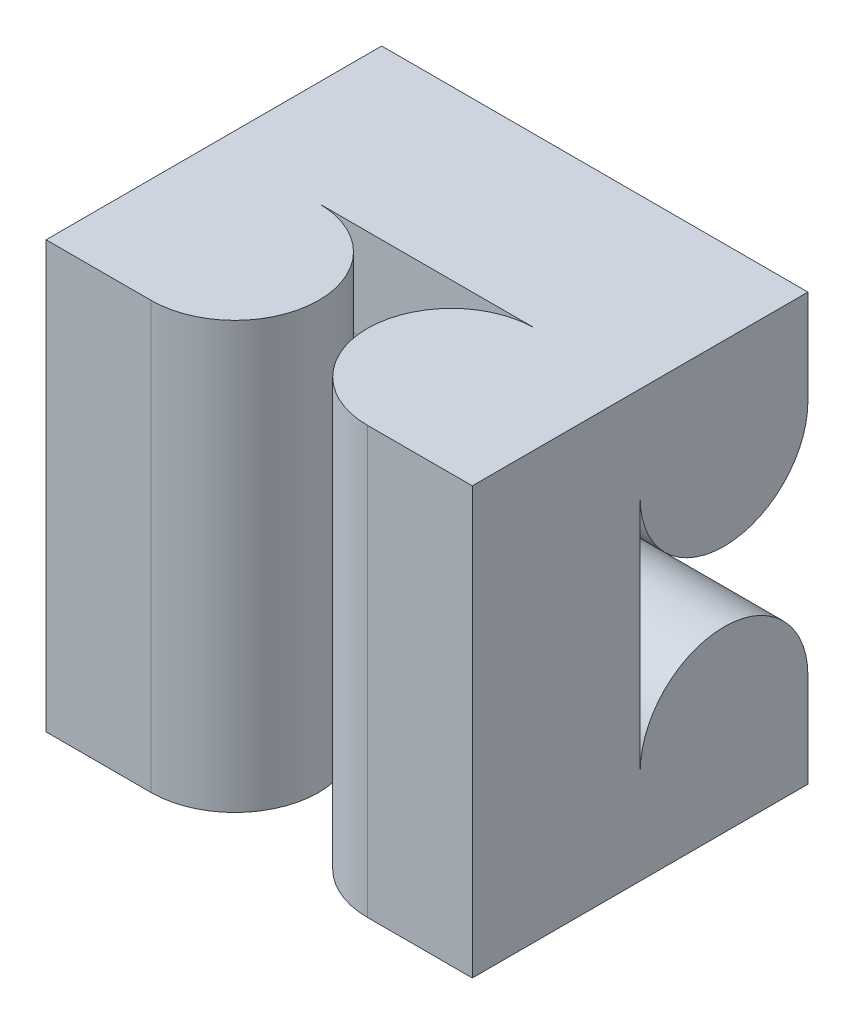
SolidWorks part; units mm, degrees
material "ABS"
ref_plane "Płaszczyzna przednia" through (0, 0, 0) normal (0, 0, 1) x (1, 0, 0)
ref_plane "Płaszczyzna górna" through (0, 0, 0) normal (0, 1, 0) x (1, 0, 0)
ref_plane "Płaszczyzna prawa" through (0, 0, 0) normal (1, 0, 0) x (0, 0, -1)
sketch "Szkic1" plane through (0, 0, 0) normal (0, 1, 0) x (1, 0, 0)
  line L3 (-0.254, 0) -> (-0.129, 0)
  line L4 (-0.129, 0.2) -> (-0.254, 0.2)
  line L5 (-0.254, 0.2) -> (-0.254, 0)
  line L6 (0, -55) -> (0, 55) construction
  line L7 (0.129, 0.2) -> (0.254, 0.2)
  line L8 (0.254, 0) -> (0.129, 0)
  line L9 (0.254, 0.2) -> (0.254, 0)
  arc A1 (-0.129, 0) -> (-0.129, 0.2) centre (-0.129, 0.1) ccw
  arc A2 (0.129, 0) -> (0.129, 0.2) centre (0.129, 0.1) cw
  point P10 (-0.029, 0.1)
  dimension "D1" = 0.2
  dimension "D2" = 0.225
  dimension "D3" = 0.508
extrude "Dodanie-wyciągnięcie1" add sketch "Szkic1" along normal blind 0.508
sketch "Szkic4" plane through (0, 0, 0) normal (1, 0, 0) x (0, 0, -1)
  line L0 (0.2, 0.508) -> (0.4, 0.508)
  line L1 (0.4, 0.508) -> (0.4, 0.3955)
  line L2 (0.2, 0.508) -> (0.2, 0) construction
  line L3 (0.2, 0.3955) -> (0.2, 0.508)
  line L6 (0.2, 0) -> (0.4, 0)
  line L7 (0.4, 0) -> (0.4, 0.1125)
  line L8 (0.2, 0.1125) -> (0.2, 0)
  arc A0 (0.4, 0.3955) -> (0.2, 0.3955) centre (0.3, 0.3955) cw
  arc A1 (0.4, 0.1125) -> (0.2, 0.1125) centre (0.3, 0.1125) ccw
  dimension "D1" = 0.2
  dimension "D2" = 0.1125
extrude "Dodanie-wyciągnięcie2" add sketch "Szkic4" along normal mid plane 0.508
